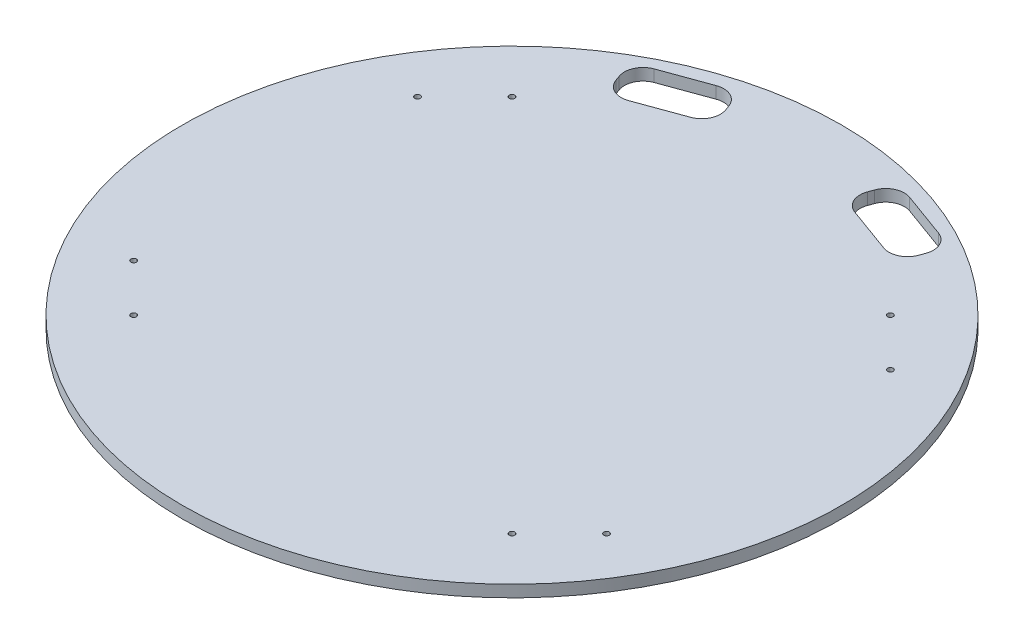
SolidWorks part; units mm, degrees
ref_plane "Front Plane" through (0, 0, 0) normal (0, 0, 1) x (1, 0, 0)
ref_plane "Top Plane" through (0, 0, 0) normal (0, 1, 0) x (1, 0, 0)
ref_plane "Right Plane" through (0, 0, 0) normal (1, 0, 0) x (0, 0, -1)
sketch "Sketch1" plane through (0, 0, 0) normal (0, 1, 0) x (1, 0, 0)
  line L1 (-76.3752, 152.7267) -> (-51.9432, 161.6192)
  line L2 (-82.3519, 139.9095) -> (-81.3259, 137.0905)
  line L3 (-68.5087, 131.1137) -> (-44.0767, 140.0063)
  line L4 (-39.1261, 155.6425) -> (-38.1, 152.8234)
  line L5 (51.9432, 161.6192) -> (76.3752, 152.7267)
  line L6 (39.1261, 155.6425) -> (38.1, 152.8234)
  line L7 (44.0767, 140.0063) -> (68.5087, 131.1137)
  line L8 (82.3519, 139.9095) -> (81.3259, 137.0905)
  circle A0 centre (0, 0) radius 177
  circle A1 centre (-101.6, -101.6) radius 1.5
  circle A2 centre (-101.6, 101.6) radius 1.5
  circle A3 centre (101.6, 101.6) radius 1.5
  circle A4 centre (101.6, -101.6) radius 1.5
  circle A5 centre (-127, 76.2) radius 1.5
  circle A6 centre (127, 76.2) radius 1.5
  circle A7 centre (127, -76.2) radius 1.5
  circle A8 centre (-127, -76.2) radius 1.5
  arc A9 (-81.3259, 137.0905) -> (-68.5087, 131.1137) centre (-71.9289, 140.5107) ccw
  arc A10 (-44.0767, 140.0063) -> (-38.1, 152.8234) centre (-47.4969, 149.4032) ccw
  arc A11 (-51.9432, 161.6192) -> (-39.1261, 155.6425) centre (-48.523, 152.2223) cw
  arc A12 (-76.3752, 152.7267) -> (-82.3519, 139.9095) centre (-72.955, 143.3297) ccw
  arc A13 (38.1, 152.8234) -> (44.0767, 140.0063) centre (47.4969, 149.4032) ccw
  arc A14 (68.5087, 131.1137) -> (81.3259, 137.0905) centre (71.9289, 140.5107) ccw
  arc A15 (76.3752, 152.7267) -> (82.3519, 139.9095) centre (72.955, 143.3297) cw
  arc A16 (51.9432, 161.6192) -> (39.1261, 155.6425) centre (48.523, 152.2223) ccw
  point P25 (-77.9057, 127.6935)
  point P30 (-42.5463, 165.0394)
  point P33 (-85.7721, 149.3065)
  point P42 (77.9057, 127.6935)
  point P45 (85.7721, 149.3065)
  point P48 (42.5463, 165.0394)
  point P51 (-20.4644, 153.1843)
  dimension "D1" = 354
  dimension "D2" = 3
  dimension "D3" = 3
  dimension "D4" = 3
  dimension "D5" = 3
  dimension "D8" = 203.2
  dimension "D13" = 3
  dimension "D14" = 3
  dimension "D15" = 3
  dimension "D16" = 3
  dimension "D26" = 10
  dimension "D29" = 10
  dimension "D6" = 203.2
  dimension "D7" = 203.2
  dimension "D9" = 203.2
  dimension "D10" = 0
  dimension "D11" = 101.6
  dimension "D12" = 101.6
  dimension "D17" = 152.4
  dimension "D18" = 152.4
  dimension "D19" = 254
  dimension "D20" = 254
  dimension "D21" = 0
  dimension "D22" = 76.2
  dimension "D23" = 127
  dimension "D24" = 46
  dimension "D25" = 23
  dimension "D27" = 46
  dimension "D28" = 23
  dimension "D30" = 38.1
  dimension "D31" = 38.1
extrude "Boss-Extrude1" add sketch "Sketch1" along normal blind 6.35
